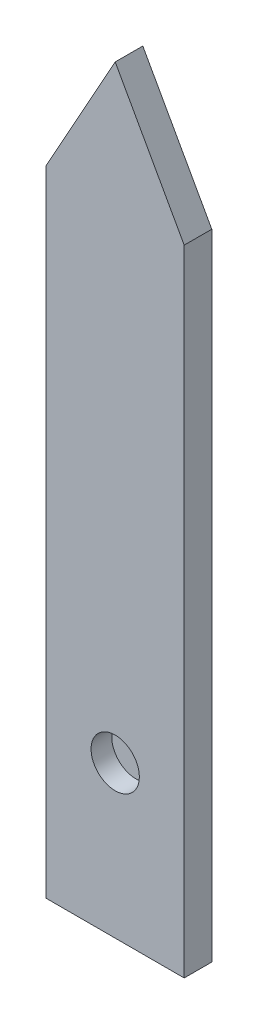
SolidWorks part; units mm, degrees
ref_plane "Ebene vorne" through (0, 0, 0) normal (0, 0, 1) x (1, 0, 0)
ref_plane "Ebene oben" through (0, 0, 0) normal (0, 1, 0) x (1, 0, 0)
ref_plane "Ebene rechts" through (0, 0, 0) normal (1, 0, 0) x (0, 0, -1)
sketch "Skizze1" plane through (0, 0, 0) normal (0, 0, 1) x (1, 0, 0)
  line L0 (0, 0) -> (20, 0)
  line L1 (20, 0) -> (20, 92)
  line L2 (20, 92) -> (10, 110)
  line L3 (10, 110) -> (0, 92)
  line L4 (0, 92) -> (0, 0)
  dimension "D1" = 20
  dimension "D2" = 92
  dimension "D3" = 92
  dimension "D4" = 110
extrude "Aufsatz-Linear austragen1" add sketch "Skizze1" along normal blind 4
sketch "Skizze3" plane through (0, 0, 4) normal (0, 0, 1) x (1, 0, 0)
  line L0 (20, 0) -> (20, 92) construction
  line L1 (0, 0) -> (20, 0) construction
  circle A0 centre (10, 22) radius 3.5
  dimension "D1" = 7
  dimension "D2" = 10
  dimension "D3" = 22
extrude "Schnitt-Linear austragen1" cut sketch "Skizze3" against normal blind 3
sketch "Skizze4" plane through (0, 0, 0) normal (0, 0, -1) x (-1, 0, 0)
  line L0 (-20, 0) -> (-20, 92) construction
  line L1 (0, 0) -> (-20, 0) construction
  circle A0 centre (-10, 98) radius 3.5
  dimension "D1" = 7
  dimension "D2" = 10
  dimension "D3" = 98
